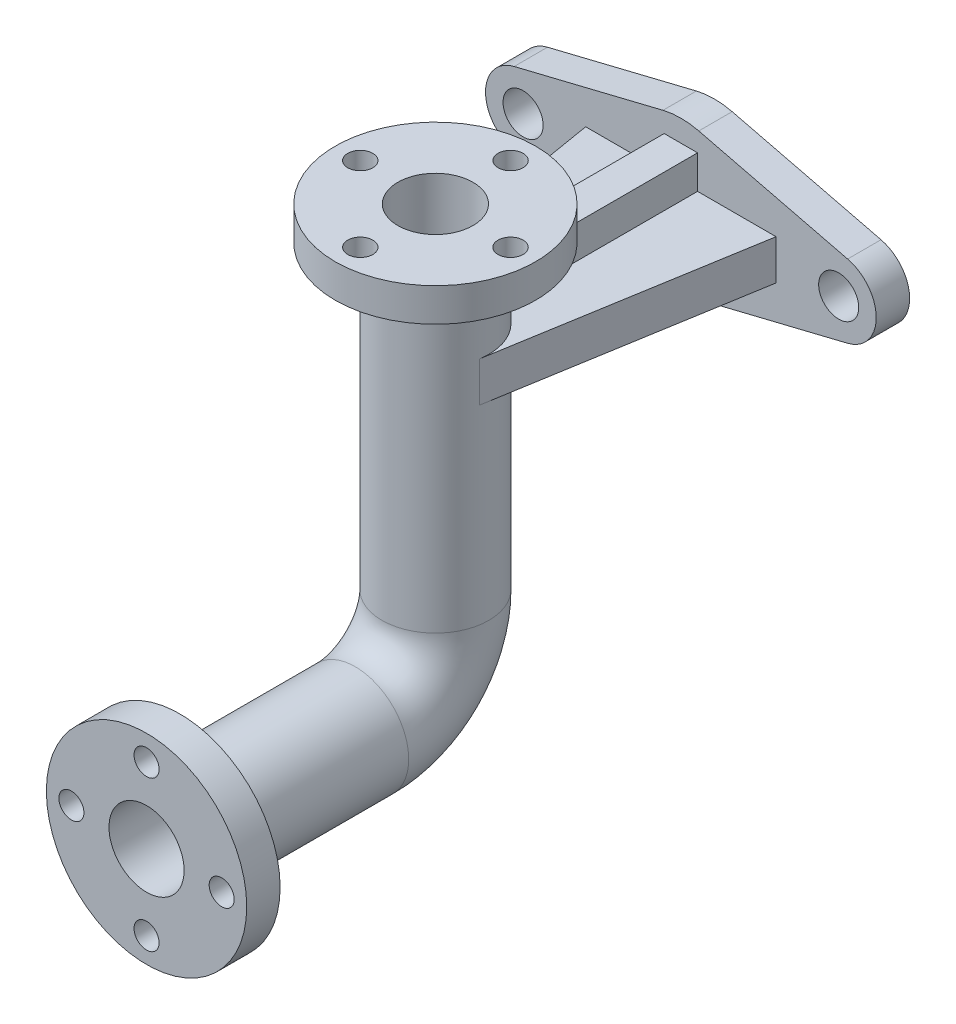
SolidWorks part; units mm, degrees
ref_plane "Front Plane" through (0, 0, 0) normal (0, 0, 1) x (1, 0, 0)
ref_plane "Top Plane" through (0, 0, 0) normal (0, 1, 0) x (1, 0, 0)
ref_plane "Right Plane" through (0, 0, 0) normal (1, 0, 0) x (0, 0, -1)
sketch "Sketch1" plane through (0, 0, 0) normal (0, 0, 1) x (1, 0, 0)
  circle A0 centre (0, 0) radius 22.5
  circle A1 centre (0, 0) radius 32
  dimension "D1" = 45
  dimension "D2" = 64
sketch "Sketch3" plane through (0, 0, 0) normal (1, 0, 0) x (0, 0, -1)
  line L0 (0, 0) -> (125, 0)
  line L1 (173, 48) -> (173, 248)
  arc A0 (125, 0) -> (173, 48) centre (125, 48) ccw
  dimension "D3" = 48
  dimension "D1" = 125
  dimension "D2" = 200
sweep "Sweep1" add profiles "Sketch1" path "Sketch3"
sketch "Sketch4" plane through (0, 248, 0) normal (0, 1, 0) x (1, 0, 0)
  circle A0 centre (0, 173) radius 60
  circle A1 centre (0, 173) radius 22.5 construction
  circle A2 centre (0, 173) radius 22.5
  dimension "D1" = 120
extrude "Boss-Extrude1" add sketch "Sketch4" against normal blind 20
sketch "Sketch5" plane through (0, 0, 0) normal (0, 0, 1) x (1, 0, 0)
  circle A0 centre (0, 0) radius 60
  circle A1 centre (0, 0) radius 22.5 construction
  circle A2 centre (0, 0) radius 22.5
  dimension "D1" = 120
extrude "Boss-Extrude2" add sketch "Sketch5" against normal blind 20
hole_wizard "Hole1" positions "Sketch6" profile "Sketch7" legacy
sketch "Sketch6" plane through (0, 0, 0) normal (0, 0, 1) x (1, 0, 0)
  point P0 (45, 0)
  point P4 (0, 0)
  dimension "D1" = 45
sketch "Sketch7" plane through (45, 0, 0) normal (1, 0, 0) x (0, -1, 0)
  line L0 (0, 0) -> (0, 20)
  line L1 (0, 20) -> (7.5, 20)
  line L2 (7.5, 20) -> (7.5, 0)
  line L3 (7.5, 0) -> (0, 0)
  line L4 (0, 110) -> (0, -10) construction
  dimension "Diameter" = 15
  dimension "Depth" = 20
pattern_circular "CirPattern1" count 4 over 360 about axis through (0, 0, 0) along (0, 0, 1) of "Hole1"
hole_wizard "Hole2" positions "Sketch8" profile "Sketch9" legacy
sketch "Sketch8" plane through (0, 248, 0) normal (0, 1, 0) x (1, 0, 0)
  line L0 (0, 173) -> (45, 173) construction
  point P0 (45, 173)
  dimension "D1" = 45
sketch "Sketch9" plane through (45, 248, -173) normal (1, 0, 0) x (0, 0, 1)
  line L0 (0, 0) -> (0, 20)
  line L1 (0, 20) -> (7.5, 20)
  line L2 (7.5, 20) -> (7.5, 0)
  line L3 (7.5, 0) -> (0, 0)
  line L4 (0, 110) -> (0, -10) construction
  dimension "Diameter" = 15
  dimension "Depth" = 20
pattern_circular "CirPattern2" count 4 over 360 about axis through (0, 0, -173) along (0, 1, 0) of "Hole2"
ref_plane "Plane1" through (0, 0, -340) normal (0, 0, 1) x (1, 0, 0)
sketch "Sketch10" plane through (0, 0, -340) normal (0, 0, 1) x (1, 0, 0)
  line L0 (60, 248) -> (-60, 248) construction
  line L1 (-99.8571, 195.8529) -> (-10.7143, 217.7059)
  line L2 (-99.8571, 152.1471) -> (-10.7143, 130.2941)
  line L3 (0, -128.15) -> (0, 128.15) construction
  line L4 (99.8571, 195.8529) -> (10.7143, 217.7059)
  line L5 (99.8571, 152.1471) -> (10.7143, 130.2941)
  arc A0 (-10.7143, 130.2941) -> (10.7143, 130.2941) centre (0, 174) ccw
  arc A1 (99.8571, 152.1471) -> (99.8571, 195.8529) centre (94.5, 174) ccw
  arc A2 (-99.8571, 195.8529) -> (-99.8571, 152.1471) centre (-94.5, 174) ccw
  arc A3 (10.7143, 217.7059) -> (-10.7143, 217.7059) centre (0, 174) ccw
  circle A4 centre (-94.5, 174) radius 12
  circle A5 centre (94.5, 174) radius 12
  dimension "D1" = 90
  dimension "D2" = 45
  dimension "D5" = 24
  dimension "D3" = 74
  dimension "D4" = 189
extrude "Boss-Extrude3" add sketch "Sketch10" along normal blind 20 separate body
ref_plane "Plane2" through (0, 174, 0) normal (0, 1, 0) x (1, 0, 0)
sketch "Sketch12" plane through (0, 174, 0) normal (0, 1, 0) x (1, 0, 0)
  line L0 (-31.5626, 167.7274) -> (-57, 320)
  line L1 (-99.8571, 320) -> (-10.7143, 320) construction
  line L2 (-57, 320) -> (57, 320)
  line L3 (10.7143, 320) -> (99.8571, 320) construction
  line L4 (57, 320) -> (31.5626, 167.7274)
  line L5 (0, 0) -> (0, 387.6974) construction
  circle A0 centre (0, 173) radius 32 construction
  arc A1 (31.5626, 167.7274) -> (-31.5626, 167.7274) centre (0, 173) ccw
  dimension "D1" = 114
extrude "Boss-Extrude4" add sketch "Sketch12" along normal mid plane 24
sketch "Sketch13" plane through (0, 0, 0) normal (1, 0, 0) x (0, 0, -1)
  line L0 (141, 228) -> (141, 48) construction
  line L1 (196, 206) -> (326, 206)
  line L2 (196, 206) -> (196, 142)
  line L3 (196, 142) -> (326, 142)
  line L4 (326, 206) -> (326, 142)
  line L6 (340, 128.7) -> (340, -128.7) construction
  line L7 (326, 174) -> (199.8913, 174) construction
  line L8 (145.0831, 174) -> (-145.0831, 174) construction
  dimension "D1" = 64
  dimension "D2" = 32
  dimension "D3" = 55
  dimension "D4" = 14
extrude "Boss-Extrude6" add sketch "Sketch13" along normal mid plane 20 contours L3 L4 L1 L2
